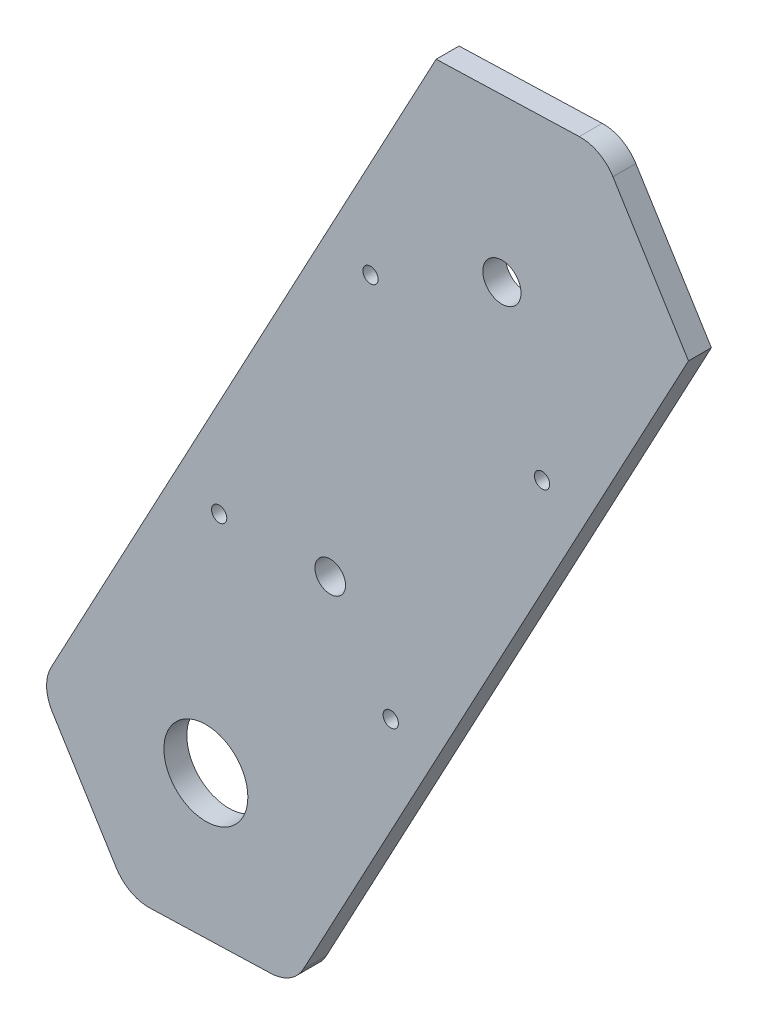
SolidWorks part; units mm, degrees
ref_plane "Front Plane" through (0, 0, 0) normal (0, 0, 1) x (1, 0, 0)
ref_plane "Top Plane" through (0, 0, 0) normal (0, 1, 0) x (1, 0, 0)
ref_plane "Right Plane" through (0, 0, 0) normal (1, 0, 0) x (0, 0, -1)
sketch "Sketch1" plane through (0, 0, 0) normal (0, 0, 1) x (1, 0, 0)
  line L6 (-91.1337, 81.8567) -> (-59.3957, 82.8728)
  line L7 (-116.6985, 113.5548) -> (-99.9495, 86.577)
  line L8 (-50.8998, 88.1473) -> (49.9945, 276.5806)
  line L9 (49.9945, 276.5806) -> (30.2002, 308.4636)
  line L10 (21.3844, 313.1839) -> (-16.1241, 311.983)
  line L11 (-117.0184, 123.5497) -> (-16.1241, 311.983)
  circle A11 centre (1.1048, 270.0128) radius 5
  circle A12 centre (-33.3325, 254.4221) radius 2
  circle A13 centre (11.6281, 230.3485) radius 2
  circle A14 centre (-28.0225, 156.2957) radius 2
  circle A15 centre (-43.8797, 180.7022) radius 4
  circle A16 centre (-72.9832, 180.3693) radius 2
  circle A17 centre (-76.4646, 119.8455) radius 11
  arc A18 (-59.3957, 82.8728) -> (-50.8998, 88.1473) centre (-59.7157, 92.8676) ccw
  arc A19 (-99.9495, 86.577) -> (-91.1337, 81.8567) centre (-91.4537, 91.8515) ccw
  arc A20 (-117.0184, 123.5497) -> (-116.6985, 113.5548) centre (-108.2026, 118.8294) ccw
  arc A21 (30.2002, 308.4636) -> (21.3844, 313.1839) centre (21.7044, 303.189) ccw
  point P1 (0, 0)
  point P5 (0, 0)
  dimension "D3" = 10
  dimension "D14" = 22
  dimension "D15" = 84
  dimension "D16" = 4
  dimension "D17" = 8
  dimension "D18" = 10
  dimension "D28" = 12
  dimension "D1" = 213.7446
  dimension "D2" = 37.5278
  dimension "D4" = 31.7543
  dimension "D5" = 60
  dimension "D6" = 60
  dimension "D7" = 60
  dimension "D8" = 60
  dimension "D9" = 120
  dimension "D10" = 120
  dimension "D11" = 50.8998
  dimension "D12" = 88.1473
  dimension "D13" = 84.7309
  dimension "D19" = 84
  dimension "D20" = 51
  dimension "D21" = 51
  dimension "D22" = 37.5
  dimension "D23" = 37.5
  dimension "D24" = 37.5
  dimension "D25" = 69.0313
  dimension "D26" = 100
  dimension "D27" = 40
  dimension "D29" = 41.0366
  dimension "D30" = 12
  dimension "D31" = 12
extrude "Boss-Extrude1" add sketch "Sketch1" along normal blind 6 separate body
